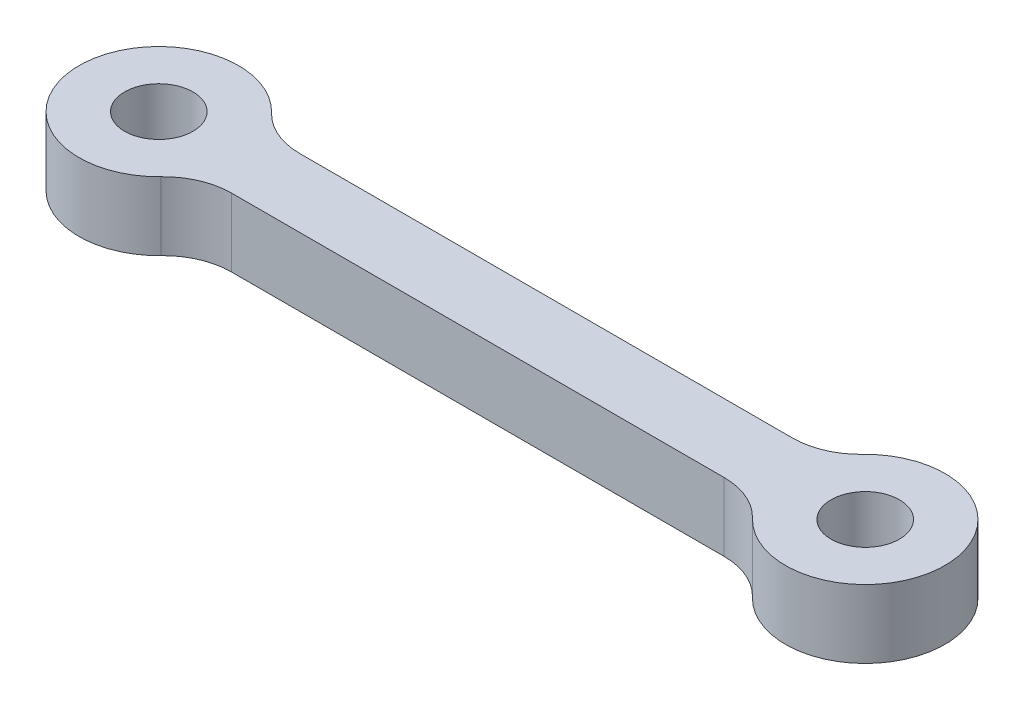
SolidWorks part; units mm, degrees
ref_plane "Ön Düzlem" through (0, 0, 0) normal (0, 0, 1) x (1, 0, 0)
ref_plane "Üst Düzlem" through (0, 0, 0) normal (0, 1, 0) x (1, 0, 0)
ref_plane "Sağ Düzlem" through (0, 0, 0) normal (1, 0, 0) x (0, 0, -1)
sketch "Çizim2" plane through (0, 0, 0) normal (0, 1, 0) x (1, 0, 0)
  line L1 (-12.3377, 1.5) -> (12.3377, 1.5)
  line L2 (-12.3377, -1.5) -> (12.3377, -1.5)
  arc A0 (-12.3377, 1.5) -> (-12.3377, -1.5) centre (-15.5, 0) ccw
  arc A1 (12.3377, -1.5) -> (12.3377, 1.5) centre (15.5, 0) ccw
  circle A2 centre (15.5, 0) radius 1.5
  circle A3 centre (-15.5, 0) radius 1.5
  point P4 (0, 0)
  dimension "D1" = 7
  dimension "D2" = 7
  dimension "D4" = 3
  dimension "D5" = 3
  dimension "D3" = 31
extrude "Yükseklik-Ekstrüzyon1" add sketch "Çizim2" along normal blind 3
fillet "Radyus1" radius 3 4 edges at (-12.3377, 1.5, -1.5) (12.3377, 1.5, -1.5) (12.3377, 1.5, 1.5) (-12.3377, 1.5, 1.5)
